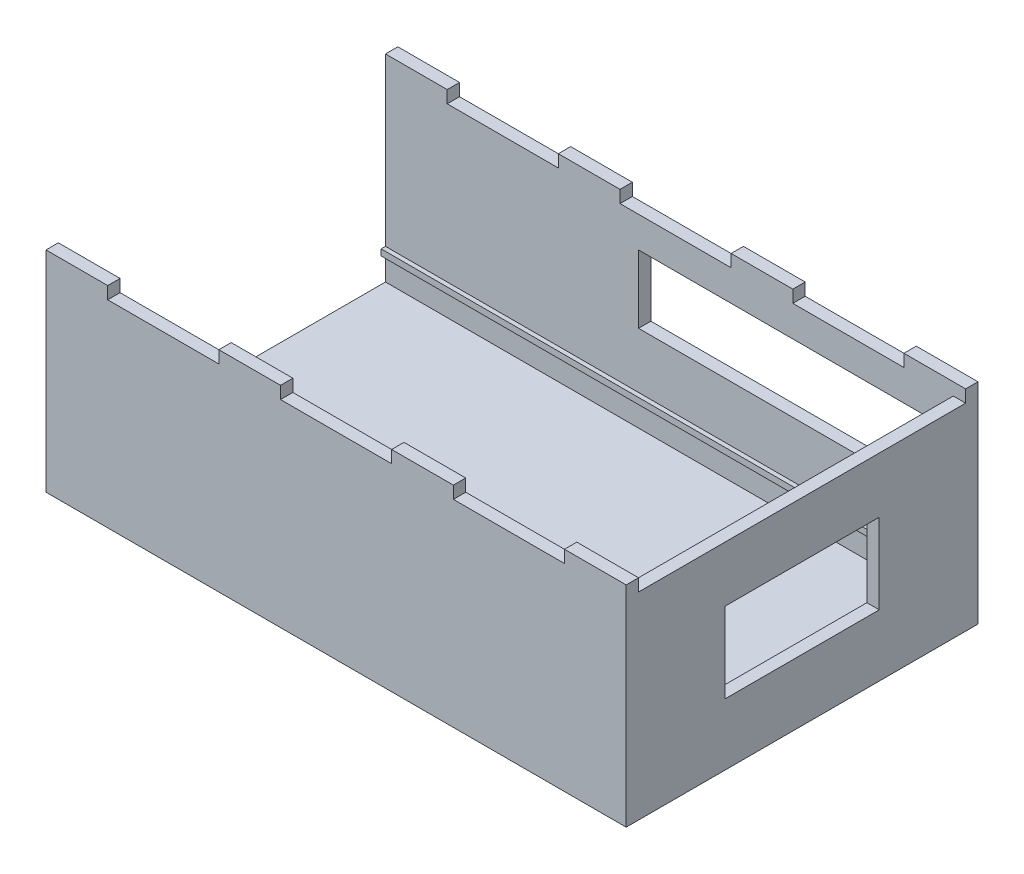
SolidWorks part; units mm, degrees
ref_plane "Front Plane" through (0, 0, 0) normal (0, 0, 1) x (1, 0, 0)
ref_plane "Top Plane" through (0, 0, 0) normal (0, 1, 0) x (1, 0, 0)
ref_plane "Right Plane" through (0, 0, 0) normal (1, 0, 0) x (0, 0, -1)
sketch "Sketch1" plane through (0, 0, 0) normal (0, 1, 0) x (1, 0, 0)
  line L0 (-56.4505, 24.5887) -> (-56.4505, -32.4113)
  line L1 (-53.9505, 22.0887) -> (35.0495, 22.0887) construction
  line L2 (-53.9505, 22.0887) -> (-53.9505, -29.9113) construction
  line L3 (-53.9505, -29.9113) -> (35.0495, -29.9113) construction
  line L4 (35.0495, 22.0887) -> (35.0495, -29.9113) construction
  line L5 (-56.4505, -32.4113) -> (37.5495, -32.4113)
  line L6 (37.5495, 24.5887) -> (37.5495, -32.4113)
  line L7 (-56.4505, 24.5887) -> (37.5495, 24.5887)
  dimension "D1" = 89
  dimension "D2" = 52
  dimension "D3" = 2.5
extrude "Boss-Extrude1" add sketch "Sketch1" along normal blind 1
sketch "Sketch2" plane through (0, 1, 0) normal (0, 1, 0) x (1, 0, 0)
  line L1 (-56.4505, 24.5887) -> (37.5495, 24.5887)
  line L2 (-56.4505, 24.5887) -> (-56.4505, 22.5887)
  line L3 (-56.4505, -32.4113) -> (37.5495, -32.4113)
  line L4 (37.5495, 24.5887) -> (37.5495, -32.4113)
  line L5 (-54.4505, -30.4113) -> (35.5495, -30.4113)
  line L6 (35.5495, 22.5887) -> (35.5495, -30.4113)
  line L7 (-54.4505, 22.5887) -> (35.5495, 22.5887)
  line L8 (-56.4505, 22.5887) -> (-54.4505, 22.5887)
  line L9 (-56.4505, -30.4113) -> (-54.4505, -30.4113)
  line L10 (-56.4505, -30.4113) -> (-56.4505, -32.4113)
  line L11 (-54.4505, 22.5887) -> (-54.4505, -30.4113) construction
  line L12 (-56.4505, 24.5887) -> (-56.4505, -32.4113) construction
  dimension "D1" = 2
extrude "Boss-Extrude3" add sketch "Sketch2" along normal blind 30
sketch "Sketch5" plane through (-56.4505, 0, 0) normal (-1, 0, 0) x (0, 0, 1)
  line L0 (-22.5887, 31) -> (-22.5887, 1) construction
  line L1 (-22.5887, 6) -> (-21.8887, 6)
  line L2 (-22.5887, 6) -> (-22.5887, 5)
  line L3 (-22.5887, 5) -> (-21.8887, 5)
  line L4 (-21.8887, 6) -> (-21.8887, 5)
  line L5 (30.4113, 31) -> (30.4113, 1) construction
  line L6 (30.4113, 6) -> (29.7113, 6)
  line L7 (30.4113, 6) -> (30.4113, 5)
  line L8 (30.4113, 5) -> (29.7113, 5)
  line L9 (29.7113, 6) -> (29.7113, 5)
  line L10 (-22.5887, 1) -> (30.4113, 1) construction
  line L11 (-22.5887, 1) -> (30.4113, 1) construction
  dimension "D1" = 1
  dimension "D2" = 1
  dimension "D3" = 0.7
  dimension "D4" = 0.7
  dimension "D5" = 4
  dimension "D6" = 4
extrude "Boss-Extrude4" add sketch "Sketch5" against normal up to surface (92 mm away) up to face at (35.5495, 16, 3.9113)
sketch "Sketch6" plane through (0, 0, -24.5887) normal (0, 0, -1) x (-1, 0, 0)
  line L0 (-37.5495, 31) -> (-37.5495, 0) construction
  line L1 (-30.5495, 26) -> (15.4505, 26)
  line L2 (-30.5495, 26) -> (-30.5495, 15)
  line L3 (-30.5495, 15) -> (15.4505, 15)
  line L4 (15.4505, 26) -> (15.4505, 15)
  point P4 (-30.5495, 20.5)
  dimension "D1" = 7
  dimension "D2" = 9
  dimension "D3" = 11
  dimension "D4" = 46
extrude "Cut-Extrude2" cut sketch "Sketch6" against normal blind 30
sketch "Sketch7" plane through (0, 31, 0) normal (0, 1, 0) x (1, 0, 0)
  line L0 (-56.4505, 22.5887) -> (35.5495, 22.5887) construction
  line L1 (-56.4505, 24.5887) -> (-46.4505, 24.5887)
  line L2 (-56.4505, 24.5887) -> (-56.4505, 22.5887)
  line L3 (-56.4505, 22.5887) -> (-46.4505, 22.5887)
  line L4 (-46.4505, 24.5887) -> (-46.4505, 22.5887)
  line L5 (37.5495, 24.5887) -> (-56.4505, 24.5887) construction
  line L6 (-28.4505, 24.5887) -> (-18.4505, 24.5887)
  line L7 (-28.4505, 24.5887) -> (-28.4505, 22.5887)
  line L8 (-28.4505, 22.5887) -> (-18.4505, 22.5887)
  line L9 (-18.4505, 24.5887) -> (-18.4505, 22.5887)
  line L10 (37.5495, -32.4113) -> (37.5495, 24.5887) construction
  line L11 (-0.4505, 24.5887) -> (9.5495, 24.5887)
  line L12 (-0.4505, 24.5887) -> (-0.4505, 22.5887)
  line L13 (-0.4505, 22.5887) -> (9.5495, 22.5887)
  line L14 (9.5495, 24.5887) -> (9.5495, 22.5887)
  line L15 (27.5495, 24.5887) -> (37.5495, 24.5887)
  line L16 (27.5495, 24.5887) -> (27.5495, 22.5887)
  line L17 (27.5495, 22.5887) -> (37.5495, 22.5887)
  line L18 (37.5495, 24.5887) -> (37.5495, 22.5887)
  line L19 (-56.4505, -32.4113) -> (37.5495, -32.4113) construction
  line L20 (-56.4505, -30.4113) -> (-46.4505, -30.4113)
  line L21 (-56.4505, -30.4113) -> (-56.4505, -32.4113)
  line L22 (-56.4505, -32.4113) -> (-46.4505, -32.4113)
  line L23 (-46.4505, -30.4113) -> (-46.4505, -32.4113)
  line L24 (35.5495, -30.4113) -> (-56.4505, -30.4113) construction
  line L25 (-28.4505, -32.4113) -> (-18.4505, -32.4113)
  line L26 (-28.4505, -32.4113) -> (-28.4505, -30.4113)
  line L27 (-28.4505, -30.4113) -> (-18.4505, -30.4113)
  line L28 (-18.4505, -32.4113) -> (-18.4505, -30.4113)
  line L30 (-0.4505, -30.4113) -> (9.5495, -30.4113)
  line L31 (-0.4505, -30.4113) -> (-0.4505, -32.4113)
  line L32 (-0.4505, -32.4113) -> (9.5495, -32.4113)
  line L33 (9.5495, -30.4113) -> (9.5495, -32.4113)
  line L34 (27.5495, -32.4113) -> (37.5495, -32.4113)
  line L35 (27.5495, -32.4113) -> (27.5495, -30.4113)
  line L36 (27.5495, -30.4113) -> (37.5495, -30.4113)
  line L37 (37.5495, -32.4113) -> (37.5495, -30.4113)
  dimension "D1" = 10
  dimension "D2" = 10
  dimension "D3" = 10
  dimension "D4" = 10
  dimension "D5" = 0
  dimension "D6" = 18
  dimension "D7" = 18
  dimension "D8" = 18
  dimension "D9" = 0
  dimension "D10" = 10
  dimension "D11" = 10
  dimension "D12" = 10
  dimension "D13" = 10
  dimension "D14" = 18
  dimension "D15" = 18
  dimension "D16" = 18
extrude "Boss-Extrude5" add sketch "Sketch7" along normal blind 2
sketch "Sketch8" plane through (37.5495, 0, 0) normal (1, 0, 0) x (0, 0, -1)
  line L0 (-32.4113, 33) -> (-32.4113, 0) construction
  line L1 (-16.4113, 22) -> (8.5887, 22)
  line L2 (-16.4113, 22) -> (-16.4113, 9)
  line L3 (-16.4113, 9) -> (8.5887, 9)
  line L4 (8.5887, 22) -> (8.5887, 9)
  line L5 (24.5887, 33) -> (24.5887, 0) construction
  line L6 (-32.4113, 0) -> (24.5887, 0) construction
  line L7 (-30.4113, 31) -> (22.5887, 31) construction
  dimension "D1" = 25
  dimension "D2" = 16
  dimension "D3" = 16
  dimension "D4" = 16
  dimension "D5" = 9
  dimension "D6" = 9
extrude "Cut-Extrude3" cut sketch "Sketch8" against normal blind 2
sketch "Sketch9" plane through (35.5495, 0, 0) normal (-1, 0, 0) x (0, 0, 1)
  line L0 (-22.5887, 31) -> (30.4113, 31) construction
  line L1 (-7.5887, 24) -> (30.4113, 24)
  line L2 (-7.5887, 24) -> (-7.5887, 23)
  line L3 (-7.5887, 23) -> (30.4113, 23)
  line L4 (30.4113, 24) -> (30.4113, 23)
  line L5 (30.4113, 33) -> (30.4113, 6) construction
  dimension "D1" = 1
  dimension "D2" = 7
  dimension "D3" = 38
  dimension "D4" = 0
extrude "Boss-Extrude6" add sketch "Sketch9" along normal blind 1
sketch "Sketch10" plane through (34.5495, 0, 0) normal (-1, 0, 0) x (0, 0, 1)
  line L0 (-7.5887, 23) -> (30.4113, 23) construction
  line L1 (30.4113, 24) -> (29.4113, 24)
  line L2 (30.4113, 24) -> (30.4113, 23)
  line L3 (30.4113, 23) -> (29.4113, 23)
  line L4 (29.4113, 24) -> (29.4113, 23)
  dimension "D1" = 1
extrude "Boss-Extrude7" add sketch "Sketch10" along normal blind 50
ref_plane "Plane2" through (0, 25.7, 0) normal (0, 1, 0) x (1, 0, 0)
sketch "Sketch11" plane through (0, 25.7, 0) normal (0, 1, 0) x (1, 0, 0)
  line L1 (34.5495, 7.5887) -> (35.5495, 7.5887)
  line L2 (34.5495, 7.5887) -> (34.5495, -29.4113)
  line L3 (34.5495, -30.4113) -> (35.5495, -30.4113)
  line L4 (35.5495, 7.5887) -> (35.5495, -30.4113)
  line L5 (35.5495, -30.4113) -> (-15.4505, -30.4113)
  line L6 (35.5495, -30.4113) -> (35.5495, -29.4113)
  line L7 (34.5495, -29.4113) -> (-15.4505, -29.4113)
  line L8 (-15.4505, -30.4113) -> (-15.4505, -29.4113)
  point P11 (34.5495, -29.4113)
extrude "Boss-Extrude8" add sketch "Sketch11" along normal blind 1 contours L5 L8 L7 L2 L1 L4
sketch "Sketch13" plane through (0, 0, 0) normal (0, -1, 0) x (1, 0, 0)
  line L1 (-56.4505, 32.4113) -> (37.5495, 32.4113)
  line L2 (-56.4505, 32.4113) -> (-56.4505, -24.5887)
  line L3 (-56.4505, -24.5887) -> (37.5495, -24.5887)
  line L4 (37.5495, 32.4113) -> (37.5495, -24.5887)
extrude "Boss-Extrude9" add sketch "Sketch13" along normal blind 1
